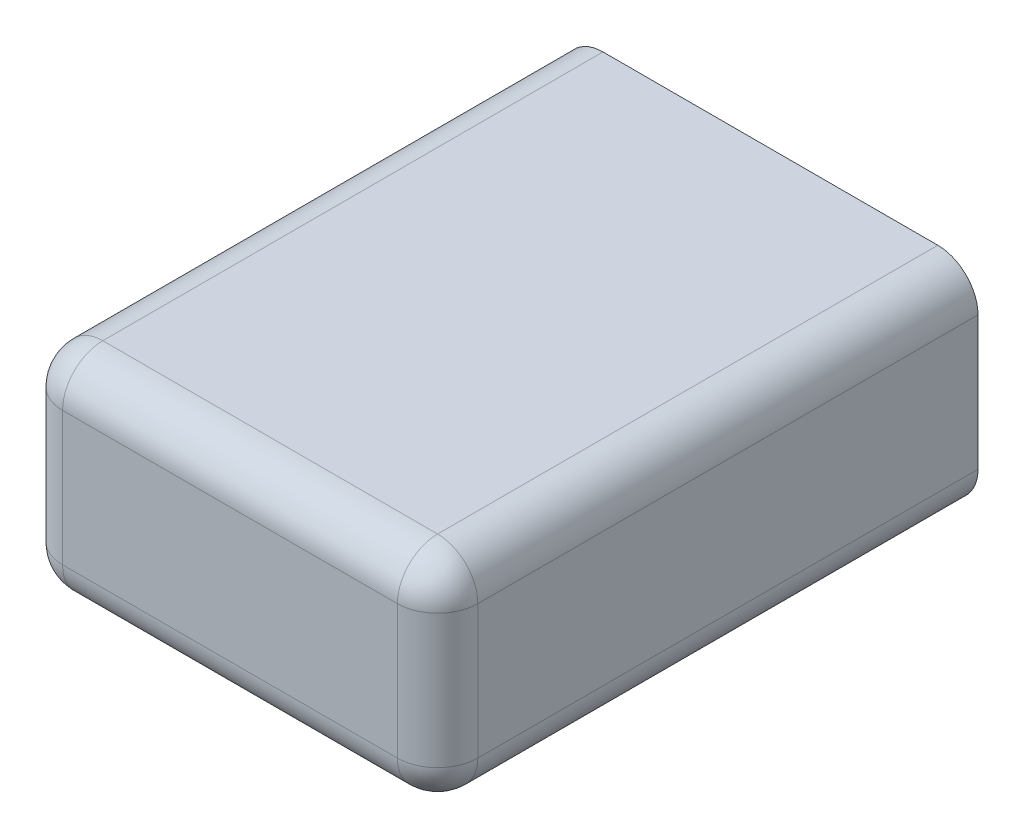
SolidWorks part; units mm, degrees
ref_plane "Piano frontale" through (0, 0, 0) normal (0, 0, 1) x (1, 0, 0)
ref_plane "Piano superiore" through (0, 0, 0) normal (0, 1, 0) x (1, 0, 0)
ref_plane "Piano destro" through (0, 0, 0) normal (1, 0, 0) x (0, 0, -1)
sketch "Schizzo1" plane through (0, 0, 0) normal (0, 0, 1) x (1, 0, 0)
  line L1 (7, -3) -> (-7, -3)
  line L2 (7, -3) -> (7, 3)
  line L3 (7, 3) -> (-7, 3)
  line L4 (-7, -3) -> (-7, 3)
  line L5 (7, -3) -> (-7, 3) construction
  line L6 (7, 3) -> (-7, -3) construction
  point P0 (0, 0)
  dimension "D1" = 14
  dimension "D2" = 6
extrude "Estrusione-Sottile1" add sketch "Schizzo1" along normal blind 20 thin thin type one direction wall 1.26
sketch "Schizzo2" plane through (0, 0, 20) normal (0, 0, 1) x (1, 0, 0)
  line L0 (8.26, -4.26) -> (8.26, 4.26) construction
  line L1 (-8.26, -4.26) -> (8.26, -4.26) construction
  line L2 (-8.26, 4.26) -> (-8.26, -4.26) construction
  line L3 (8.26, 4.26) -> (-8.26, 4.26) construction
  line L4 (8.26, -4.26) -> (8.26, 4.26)
  line L5 (-8.26, -4.26) -> (8.26, -4.26)
  line L6 (-8.26, 4.26) -> (-8.26, -4.26)
  line L7 (8.26, 4.26) -> (-8.26, 4.26)
extrude "Estrusione-Estrusione1" add sketch "Schizzo2" along normal blind 1.5
fillet "Raccordo1" radius 1.6 8 edges at (-8.26, -4.26, 10.75) (8.26, 4.26, 10.75) (8.26, -4.26, 10.75) (0, -4.26, 21.5) (8.26, 0, 21.5) (0, 4.26, 21.5) (-8.26, 0, 21.5) (-8.26, 4.26, 10.75)
fillet "Raccordo2" radius 0.5 8 edges at (-7, 3, 10) (-7, -3, 10) (-7, 0, 20) (0, -3, 20) (7, -3, 10) (7, 0, 20) (0, 3, 20) (7, 3, 10)
